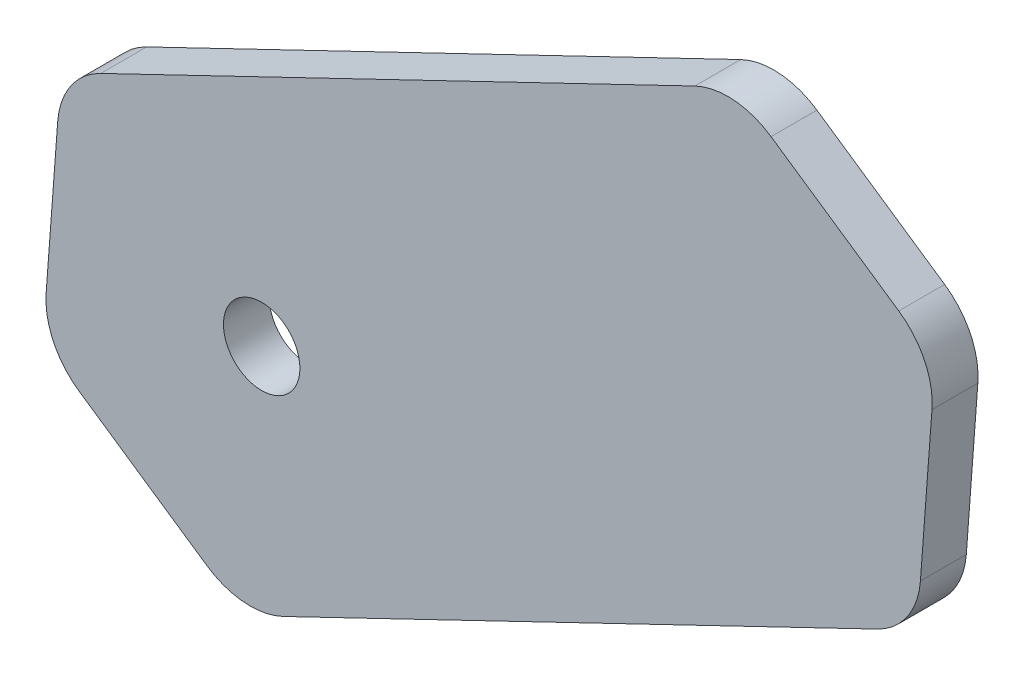
SolidWorks part; units mm, degrees
ref_plane "Front Plane" through (0, 0, 0) normal (0, 0, 1) x (1, 0, 0)
ref_plane "Top Plane" through (0, 0, 0) normal (0, 1, 0) x (1, 0, 0)
ref_plane "Right Plane" through (0, 0, 0) normal (1, 0, 0) x (0, 0, -1)
sketch "Sketch2" plane through (0, 0, 0) normal (0, 0, 1) x (1, 0, 0)
  line L8 (-70.3638, 318.0858) -> (-87.0622, 329.4703) construction
  line L9 (-67.5347, 288.9227) -> (-66.0248, 309.0762) construction
  line L11 (-177.5012, 255.3897) -> (-160.8028, 244.0053) construction
  line L12 (-180.3303, 284.5529) -> (-181.8402, 264.3993) construction
  line L13 (-97.0343, 330.2174) -> (-174.6972, 292.8153) construction
  line L14 (-174.6972, 292.8153) -> (-97.0343, 330.2174)
  line L15 (-87.0622, 329.4703) -> (-70.3638, 318.0858)
  line L16 (-66.0248, 309.0762) -> (-67.5347, 288.9227)
  line L17 (-73.1678, 280.6602) -> (-150.8307, 243.2582)
  line L18 (-160.8028, 244.0053) -> (-177.5012, 255.3897)
  line L19 (-181.8402, 264.3993) -> (-180.3303, 284.5529)
  arc A0 (-180.3303, 284.5529) -> (-174.6972, 292.8153) centre (-170.3582, 283.8057) cw
  arc A1 (-97.0343, 330.2174) -> (-87.0622, 329.4703) centre (-92.6953, 321.2078) cw
  arc A2 (-67.5347, 288.9227) -> (-73.1678, 280.6602) centre (-77.5068, 289.6698) cw
  arc A3 (-70.3638, 318.0858) -> (-66.0248, 309.0762) centre (-75.9968, 309.8233) cw
  arc A4 (-150.8307, 243.2582) -> (-160.8028, 244.0053) centre (-155.1697, 252.2678) cw
  arc A5 (-177.5012, 255.3897) -> (-181.8402, 264.3993) centre (-171.8682, 263.6522) cw
  circle A12 centre (-153.6608, 272.4234) radius 5
  point P11 (-180.8778, 259.3132)
  point P13 (0, 0)
  point P19 (0, 0)
  point P21 (0, 0)
  point P22 (0, 0)
  point P24 (0, 0)
  point P26 (0, 0)
  point P27 (52.9437, 341.3949)
  dimension "D1" = 60
  dimension "D2" = 60
  dimension "D3" = 10
  dimension "D5" = 60
  dimension "D8" = 10
  dimension "D9" = 20.21
  dimension "D4" = 86.2
  dimension "D6" = 60
  dimension "D7" = 60
  dimension "D10" = 27.5
  dimension "D11" = 243.2582
  dimension "D12" = 150.8307
  dimension "D13" = 284.6115
  dimension "D14" = 30.21
extrude "Boss-Extrude2" add sketch "Sketch2" along normal blind 6 separate body
